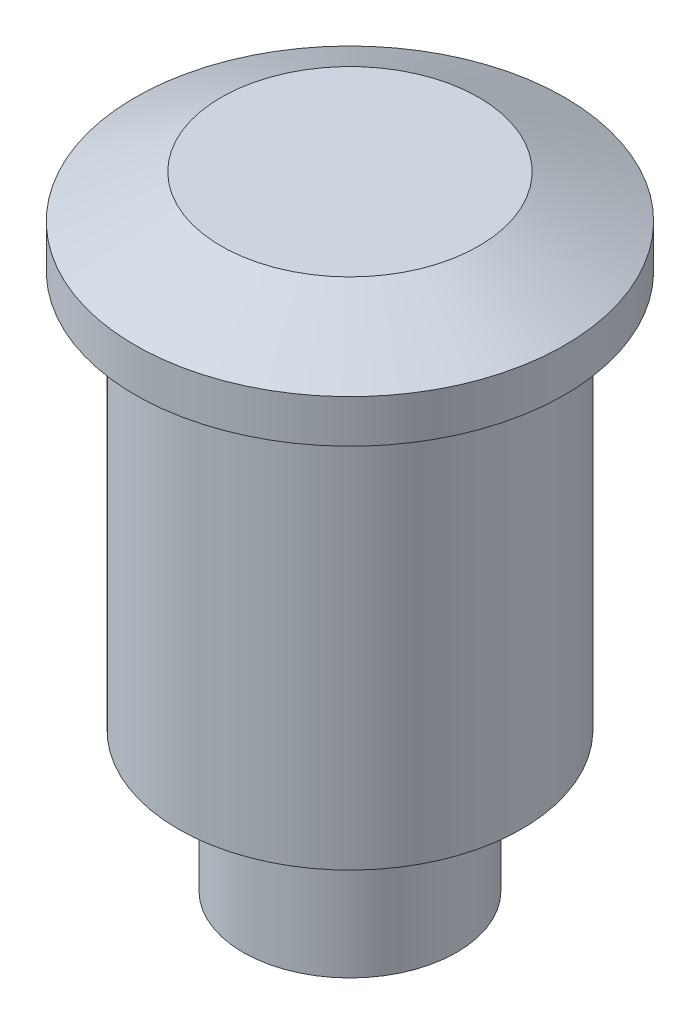
SolidWorks part; units mm, degrees
ref_plane "Plan de face" through (0, 0, 0) normal (0, 0, 1) x (1, 0, 0)
ref_plane "Plan de dessus" through (0, 0, 0) normal (0, 1, 0) x (1, 0, 0)
ref_plane "Plan de droite" through (0, 0, 0) normal (1, 0, 0) x (0, 0, -1)
sketch "Esquisse1" plane through (0, 0, 0) normal (0, 0, 1) x (1, 0, 0)
  line L0 (0, 0) -> (0, 84.0473) construction
  line L1 (0, 59.82) -> (3, 59.82)
  line L2 (3, 59.82) -> (5, 58.82)
  line L3 (5, 58.82) -> (5, 57.82)
  line L4 (5, 57.82) -> (4, 57.82)
  line L5 (4, 57.82) -> (4, 48.5655)
  line L6 (4, 48.5655) -> (2.486, 48.5655)
  line L7 (2.486, 48.5655) -> (2.486, 45.32)
  line L8 (2.486, 45.32) -> (0, 45.32)
  line L9 (0, 59.82) -> (0, 45.32)
  dimension "D1" = 2
  dimension "D2" = 5
  dimension "D3" = 12.5
  dimension "D4" = 4
  dimension "D5" = 3
  dimension "D6" = 1
revolve "Révolution1" add sketch "Esquisse1" angle 360 about L0
